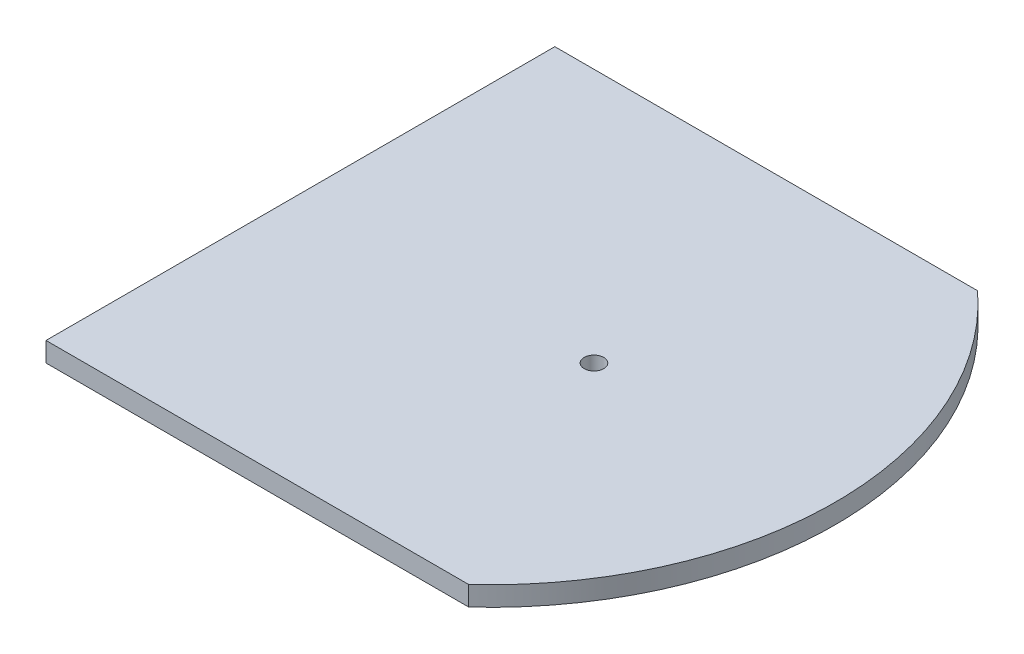
SolidWorks part; units mm, degrees
ref_plane "Front Plane" through (0, 0, 0) normal (0, 0, 1) x (1, 0, 0)
ref_plane "Top Plane" through (0, 0, 0) normal (0, 1, 0) x (1, 0, 0)
ref_plane "Right Plane" through (0, 0, 0) normal (1, 0, 0) x (0, 0, -1)
sketch "Sketch1" plane through (0, 0, 0) normal (0, 1, 0) x (1, 0, 0)
  line L0 (0, -65) -> (-15.2207, -65) construction
  line L1 (0, 0) -> (108, 0)
  line L2 (0, 0) -> (0, -130)
  line L3 (0, -130) -> (108, -130)
  arc A0 (108, 0) -> (108, -130) centre (48.5152, -65) cw
  circle A1 centre (75, -65) radius 2.5
extrude "Boss-Extrude1" add sketch "Sketch1" along normal blind 5
